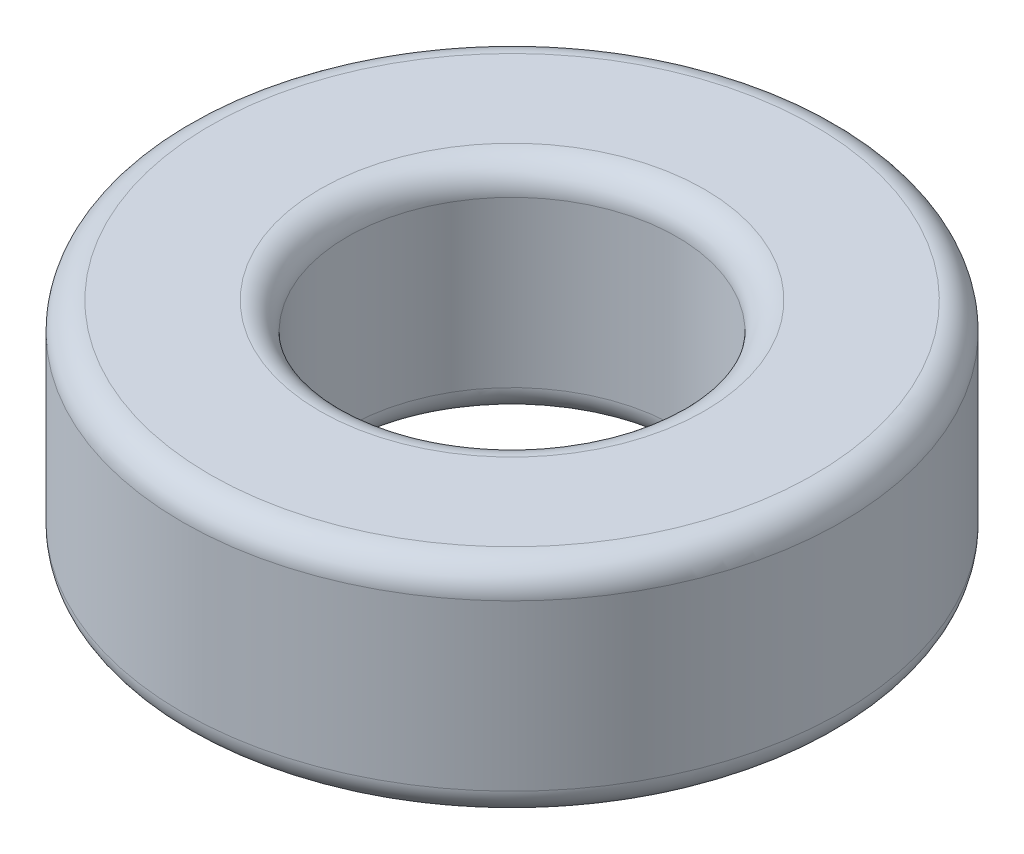
SolidWorks part; units mm, degrees
ref_plane "前视基准面" through (0, 0, 0) normal (0, 0, 1) x (1, 0, 0)
ref_plane "上视基准面" through (0, 0, 0) normal (0, 1, 0) x (1, 0, 0)
ref_plane "右视基准面" through (0, 0, 0) normal (1, 0, 0) x (0, 0, -1)
sketch "草图1" plane through (0, 0, 0) normal (0, 1, 0) x (1, 0, 0)
  circle A0 centre (0, 0) radius 3
  circle A1 centre (0, 0) radius 6
  dimension "D1" = 12
  dimension "D2" = 6
extrude "凸台-拉伸1" add sketch "草图1" along normal blind 4
fillet "圆角1" radius 0.5 4 edges at (0, 0, 3) (0, 0, 6) (0, 4, 6) (0, 4, 3)
